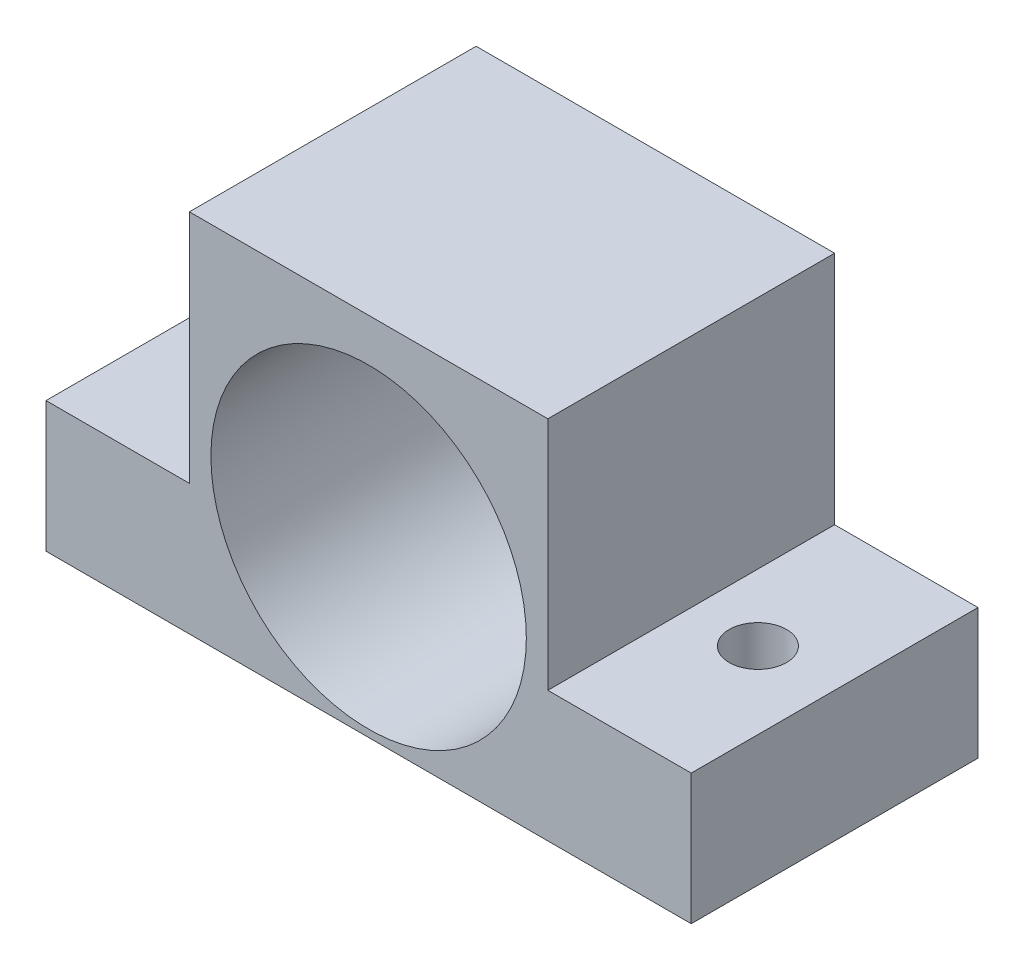
SolidWorks part; units mm, degrees
material "ABS"
ref_plane "Front Plane" through (0, 0, 0) normal (0, 0, 1) x (1, 0, 0)
ref_plane "Top Plane" through (0, 0, 0) normal (0, 1, 0) x (1, 0, 0)
ref_plane "Right Plane" through (0, 0, 0) normal (1, 0, 0) x (0, 0, -1)
sketch "Sketch1" plane through (0, 0, 0) normal (0, 0, 1) x (1, 0, 0)
  line L0 (185.6419, -17.5) -> (-64.3581, -17.5) construction
  line L1 (-11.4483, 8) -> (13.5517, 8)
  line L2 (-11.4483, 8) -> (-11.4483, -17.5)
  line L3 (-11.4483, -17.5) -> (13.5517, -17.5)
  line L4 (13.5517, 8) -> (13.5517, -17.5)
  line L5 (-11.4483, 8) -> (13.5517, -17.5) construction
  line L6 (-11.4483, -17.5) -> (13.5517, 8) construction
  line L7 (13.5517, -17.5) -> (23.5517, -17.5)
  line L8 (13.5517, -17.5) -> (13.5517, -8.4)
  line L9 (13.5517, -8.4) -> (23.5517, -8.4)
  line L10 (23.5517, -17.5) -> (23.5517, -8.4)
  line L11 (13.5517, -17.5) -> (23.5517, -8.4) construction
  line L12 (13.5517, -8.4) -> (23.5517, -17.5) construction
  line L13 (-11.4483, -17.5) -> (-21.4483, -17.5)
  line L14 (-11.4483, -17.5) -> (-11.4483, -8.4)
  line L15 (-11.4483, -8.4) -> (-21.4483, -8.4)
  line L16 (-21.4483, -17.5) -> (-21.4483, -8.4)
  line L17 (-11.4483, -17.5) -> (-21.4483, -8.4) construction
  line L18 (-11.4483, -8.4) -> (-21.4483, -17.5) construction
  circle A0 centre (1.0517, -6) radius 4.1
  circle A1 centre (1.0517, -6) radius 11
  circle A2 centre (1.0517, -6) radius 4 construction
  point P8 (1.0517, -6)
  point P14 (18.5517, -12.95)
  point P16 (-16.4483, -12.95)
  dimension "D4" = 8.2
  dimension "D5" = 22
  dimension "D1" = 14
  dimension "D3" = 25
  dimension "D6" = 10
  dimension "D7" = 9.1
  dimension "D8" = 10
  dimension "D10" = 12.5
extrude "Boss-Extrude1" add sketch "Sketch1" along normal blind 20 contours L4 L1 L2 L3 A1 | L16 L13 L2 L15 | L7 L10 L9 L4
sketch "Sketch2" plane through (0, -8.4, 0) normal (0, 1, 0) x (1, 0, 0)
  line L1 (-11.4483, -20) -> (-21.4483, -20)
  line L4 (23.5517, -20) -> (23.5517, 0)
  circle A0 centre (-16.7988, -10) radius 2
  circle A1 centre (18.2012, -10) radius 2
  circle A2 centre (18.2012, -10) radius 2 construction
  circle A3 centre (-16.7988, -10) radius 2 construction
  dimension "D1" = 4
  dimension "D2" = 4
extrude "Cut-Extrude1" cut sketch "Sketch2" against normal blind 9
